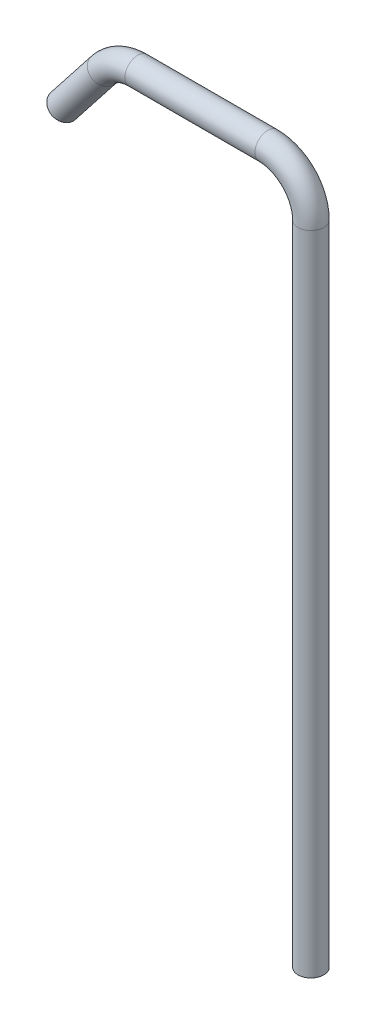
SolidWorks part; units mm, degrees
ref_plane "Front Plane" through (0, 0, 0) normal (0, 0, 1) x (1, 0, 0)
ref_plane "Top Plane" through (0, 0, 0) normal (0, 1, 0) x (1, 0, 0)
ref_plane "Right Plane" through (0, 0, 0) normal (1, 0, 0) x (0, 0, -1)
sketch "Sketch1" plane through (0, 0, 0) normal (0, 0, 1) x (1, 0, 0)
  line L1 (0, 0) -> (0, 100)
  line L3 (-10, 110) -> (-40.1378, 110)
  line L4 (-48.0028, 106.1759) -> (-57.4055, 94.2016)
  arc A0 (-40.1378, 110) -> (-48.0028, 106.1759) centre (-40.1378, 100) ccw
  arc A1 (0, 100) -> (-10, 110) centre (-10, 100) ccw
  point P7 (-45, 110)
  point P10 (0, 110)
  dimension "D3" = 10
  dimension "D1" = 110
  dimension "D2" = 45
sketch "Sketch2" plane through (0, 0, 0) normal (0, 1, 0) x (1, 0, 0)
  circle A0 centre (0, 0) radius 3
  dimension "D1" = 6
sweep "Sweep1" add profiles "Sketch2" path "Sketch1"
sketch "Sketch4" plane through (0, 0, 0) normal (0, -1, 0) x (1, 0, 0)
  circle A0 centre (0, 0) radius 3
extrude "Boss-Extrude1" add sketch "Sketch4" along normal blind 30
sketch "Sketch5" plane through (0, -30, 0) normal (0, -1, 0) x (1, 0, 0)
  circle A0 centre (0, 0) radius 3
extrude "Boss-Extrude2" add sketch "Sketch5" along normal blind 20
